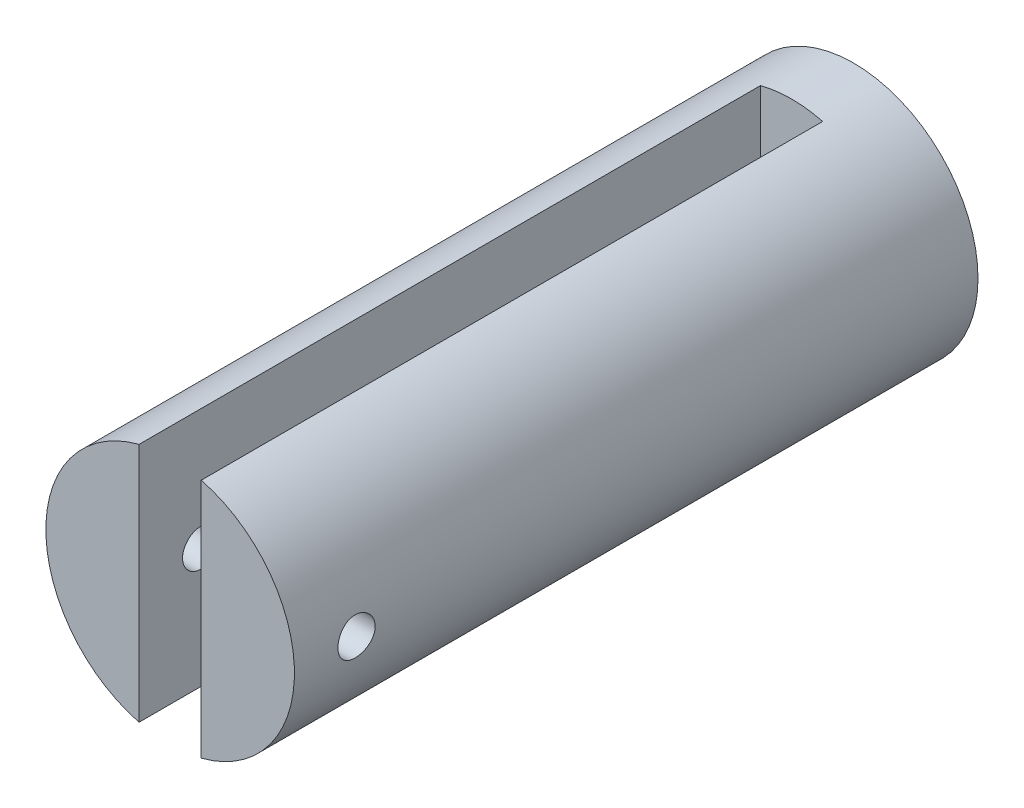
SolidWorks part; units mm, degrees
ref_plane "Alzado" through (0, 0, 0) normal (0, 0, 1) x (1, 0, 0)
ref_plane "Planta" through (0, 0, 0) normal (0, 1, 0) x (1, 0, 0)
ref_plane "Vista lateral" through (0, 0, 0) normal (1, 0, 0) x (0, 0, -1)
sketch "Croquis1" plane through (0, 0, 0) normal (0, 0, 1) x (1, 0, 0)
  circle A0 centre (0, 0) radius 2.5
  circle A1 centre (0, 0) radius 10
  dimension "D1" = 5
  dimension "D2" = 20
extrude "Saliente-Extruir1" add sketch "Croquis1" along normal blind 5
sketch "Croquis2" plane through (0, 0, 5) normal (0, 0, 1) x (1, 0, 0)
  line L2 (-2.5, -9.6825) -> (-2.5, 9.6825)
  line L4 (2.5, -9.6825) -> (2.5, 9.6825)
  circle A0 centre (0, 0) radius 10 construction
  arc A1 (2.5, -9.6825) -> (2.5, 9.6825) centre (0, 0) ccw
  arc A2 (-2.5, 9.6825) -> (-2.5, -9.6825) centre (0, 0) ccw
  dimension "D1" = 2.5
  dimension "D2" = 5
extrude "Saliente-Extruir2" add sketch "Croquis2" along normal blind 50
sketch "Croquis3" plane through (2.5, 0, 0) normal (-1, 0, 0) x (0, 0, 1)
  line L0 (0, 0) -> (55, 0) construction
  line L1 (55, -9.6825) -> (55, 9.6825) construction
  circle A0 centre (50, 0) radius 1.5
  dimension "D1" = 3
  dimension "D2" = 5
extrude "Cortar-Extruir1" cut sketch "Croquis3" against normal mid plane 40
ref_plane "Plano1" through (0, 0, 45) normal (0, 0, 1) x (1, 0, 0)
sketch "Croquis6" plane through (0, 0, 45) normal (0, 0, 1) x (1, 0, 0)
  circle A0 centre (0, 0) radius 3.75
  dimension "D1" = 7.5
extrude "Cortar-Extruir3" cut sketch "Croquis6" against normal blind 42.5
